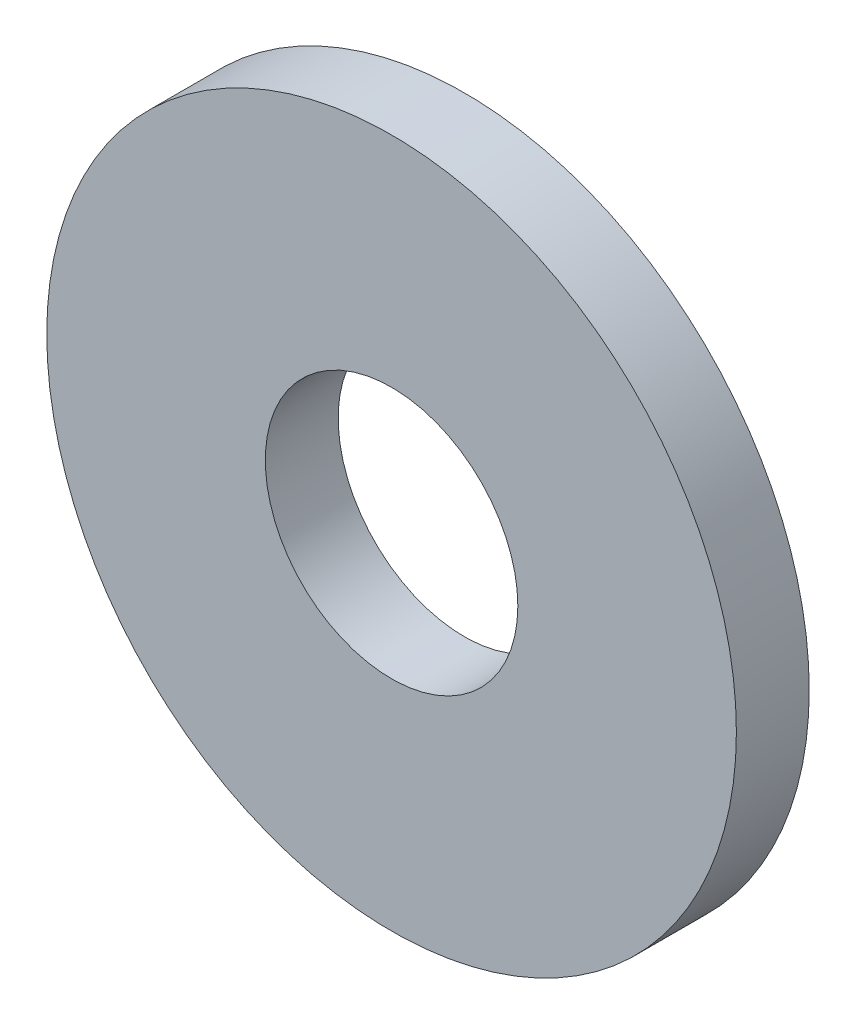
SolidWorks part; units mm, degrees
material "Silica Phenolic"
ref_plane "Piano frontale" through (0, 0, 0) normal (0, 0, 1) x (1, 0, 0)
ref_plane "Piano superiore" through (0, 0, 0) normal (0, 1, 0) x (1, 0, 0)
ref_plane "Piano destro" through (0, 0, 0) normal (1, 0, 0) x (0, 0, -1)
sketch "Schizzo1" plane through (0, 0, 0) normal (0, 0, 1) x (1, 0, 0)
  circle A0 centre (0, 0) radius 26
  circle A1 centre (0, 0) radius 71
  dimension "D1" = 52
  dimension "D2" = 142
extrude "Estrusione-Estrusione1" add sketch "Schizzo1" along normal blind 15
